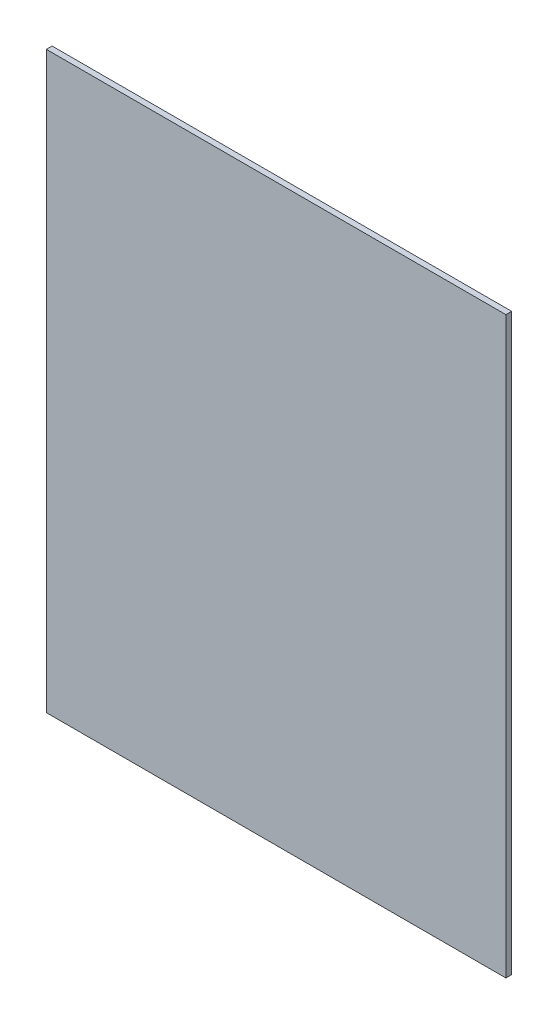
SolidWorks part; units mm, degrees
material "Фанера, берёза, ФСФ ВВ/С ГОСТ 3916.1-96"
ref_plane "Спереди" through (0, 0, 0) normal (0, 0, 1) x (1, 0, 0)
ref_plane "Сверху" through (0, 0, 0) normal (0, 1, 0) x (1, 0, 0)
ref_plane "Справа" through (0, 0, 0) normal (1, 0, 0) x (0, 0, -1)
sketch "Эскиз1" plane through (0, 0, 0) normal (0, 0, 1) x (1, 0, 0)
  line L1 (0, 0) -> (320, 0)
  line L2 (0, 0) -> (0, 400)
  line L3 (0, 400) -> (320, 400)
  line L4 (320, 0) -> (320, 400)
  dimension "D1" = 400
  dimension "D2" = 320
extrude "Бобышка-Вытянуть1" add sketch "Эскиз1" along normal blind 4
